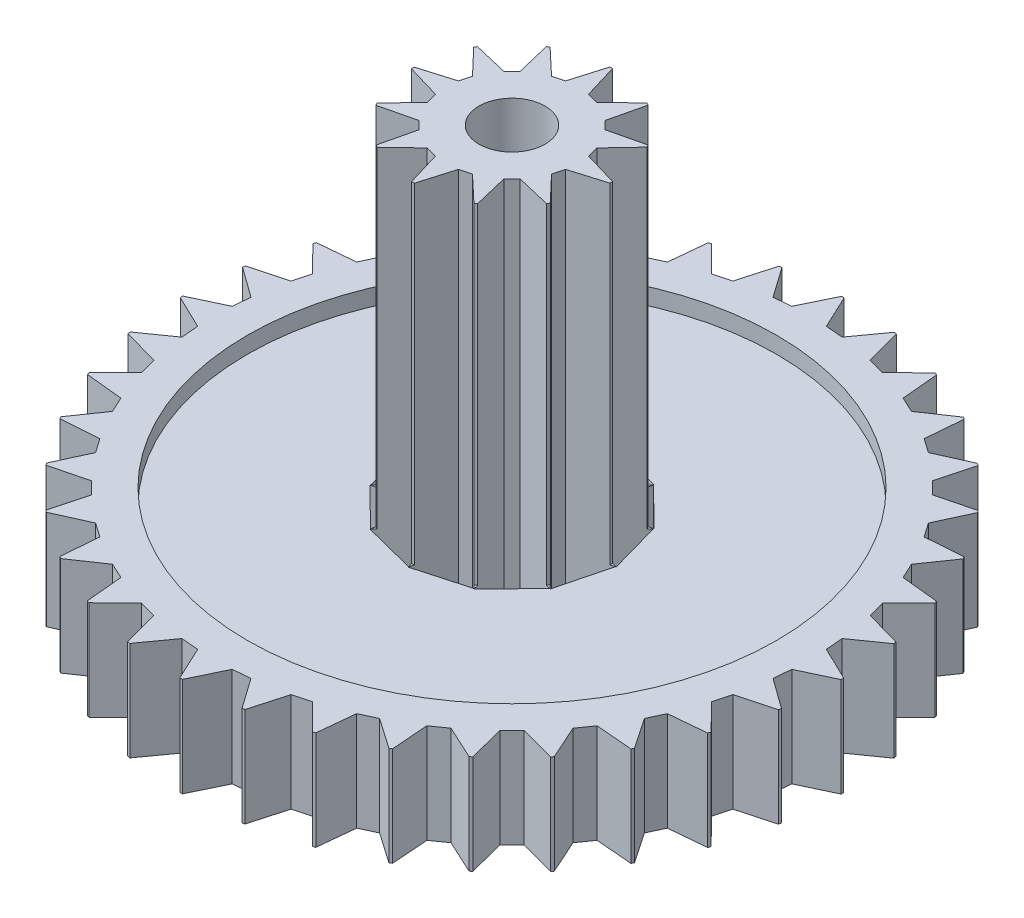
SolidWorks part; units mm, degrees
ref_plane "Front Plane" through (0, 0, 0) normal (0, 0, 1) x (1, 0, 0)
ref_plane "Top Plane" through (0, 0, 0) normal (0, 1, 0) x (1, 0, 0)
ref_plane "Right Plane" through (0, 0, 0) normal (1, 0, 0) x (0, 0, -1)
sketch "Sketch2" plane through (0, 0, 0) normal (0, 1, 0) x (1, 0, 0)
  circle A0 centre (0, 0) radius 5
extrude "Boss-Extrude1" add sketch "Sketch2" along normal blind 1.5
sketch "Sketch3" plane through (0, 1.5, 0) normal (0, 1, 0) x (1, 0, 0)
  line L0 (0, 0) -> (0, 5.8828) construction
  line L1 (0, 0) -> (0.4167, 7.1541) construction
  line L2 (0, 0) -> (0.6915, 5.9163) construction
  line L3 (0, 0) -> (1.1608, 6.5832) construction
  circle A0 centre (0, 0) radius 4.5
  dimension "D1" = 3.333
  dimension "D2" = 3.333
  dimension "D3" = 3.333
sketch "Sketch4" plane through (0, 1.5, 0) normal (0, 1, 0) x (1, 0, 0)
  line L0 (0.2617, 4.4924) -> (0, 5.0489)
  line L1 (0, 0) -> (0.4167, 7.1541) construction
  line L3 (0, 0) -> (0, 5.8828) construction
  line L5 (0, 5.0489) -> (0.8741, 4.9574)
  line L6 (0, 0) -> (0.6915, 5.9163) construction
  line L7 (0.5224, 4.4696) -> (0.2617, 4.4924)
  line L8 (0, 0) -> (1.1608, 6.5832) construction
  line L9 (0.8741, 4.9574) -> (0.5224, 4.4696)
  circle A0 centre (0, 0) radius 4.5 construction
extrude "Cut-Extrude1" cut sketch "Sketch4" against normal through all
sketch "Sketch5" plane through (0, 0, 0) normal (1, 0, 0) x (0, 0, -1)
  line L0 (0, 0) -> (0, 2.2331) construction
pattern_circular "CirPattern1" count 36 over 360 about axis through (0, 0, 0) along (0, 1, 0) of "Cut-Extrude1"
sketch "Sketch6" plane through (0, 1.5, 0) normal (0, 1, 0) x (1, 0, 0)
  circle A0 centre (0, 0) radius 4
extrude "Cut-Extrude2" cut sketch "Sketch6" against normal blind 0.25
sketch "Sketch7" plane through (0, 1.5, 0) normal (0, 1, 0) x (1, 0, 0)
  circle A0 centre (0, 0) radius 0.5
extrude "Cut-Extrude3" cut sketch "Sketch7" against normal through all
sketch "Sketch8" plane through (0, 0, 0) normal (0, -1, 0) x (-1, 0, 0)
  circle A0 centre (0, 0) radius 4
  circle A1 centre (0, 0) radius 1
extrude "Cut-Extrude4" cut sketch "Sketch8" against normal blind 0.25
sketch "Sketch9" plane through (0, 1.25, 0) normal (0, 1, 0) x (1, 0, 0)
  circle A0 centre (0, 0) radius 1.5
extrude "Boss-Extrude2" add sketch "Sketch9" along normal blind 5
sketch "Sketch10" plane through (0, 6.25, 0) normal (0, 1, 0) x (1, 0, 0)
  circle A0 centre (0, 0) radius 0.5
extrude "Cut-Extrude5" cut sketch "Sketch10" against normal through all
sketch "Sketch11" plane through (0, 6.25, 0) normal (0, 1, 0) x (1, 0, 0)
  line L0 (0, 0) -> (-2.1437, 0) construction
  line L1 (0, 0) -> (-2.1634, 0.3815) construction
  line L2 (0, 0) -> (-2.029, 0.7385) construction
  line L3 (0, 0) -> (-1.7892, 1.033) construction
  line L4 (-0.9848, 0.1736) -> (-1.5653, 0)
  line L5 (-1.5653, 0) -> (-1.3636, 0.7873)
  line L6 (-1.3636, 0.7873) -> (-0.9397, 0.342)
  line L7 (-0.9848, 0.1736) -> (-0.9397, 0.342)
  circle A0 centre (0, 0) radius 1
  dimension "D1" = 10
  dimension "D2" = 10
  dimension "D3" = 10
extrude "Cut-Extrude6" cut sketch "Sketch11" against normal blind 6.25 contours L4 L5 L6 L7
pattern_circular "CirPattern2" count 12 over 360 about axis through (0, 0, 0) along (0, 1, 0) of "Cut-Extrude6"
